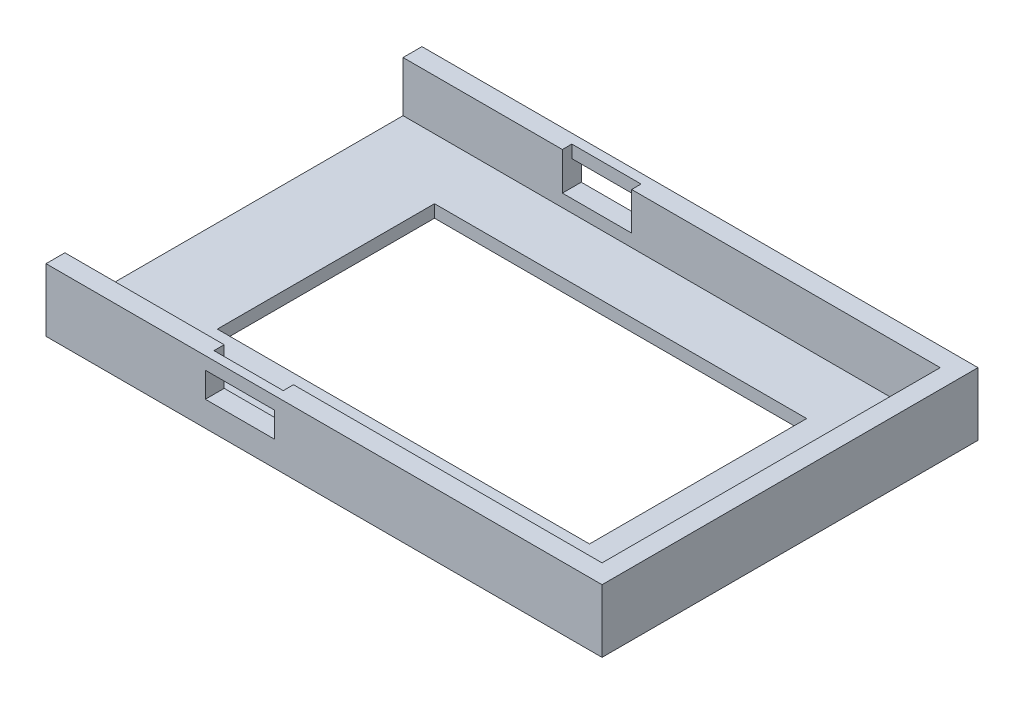
SolidWorks part; units mm, degrees
ref_plane "前视基准面" through (0, 0, 0) normal (0, 0, 1) x (1, 0, 0)
ref_plane "上视基准面" through (0, 0, 0) normal (0, 1, 0) x (1, 0, 0)
ref_plane "右视基准面" through (0, 0, 0) normal (1, 0, 0) x (0, 0, -1)
sketch "草图1" plane through (0, 0, 0) normal (0, 1, 0) x (1, 0, 0)
  line L0 (-41.15, -26.85) -> (41.15, -26.85)
  line L1 (-41.15, -26.85) -> (-41.15, 26.85)
  line L2 (41.15, -26.85) -> (41.15, 26.85)
  line L3 (-41.15, 26.85) -> (41.15, 26.85)
  line L4 (-41.15, -26.85) -> (41.15, 26.85) construction
  line L5 (41.15, -26.85) -> (-41.15, 26.85) construction
  line L6 (-44.15, -29.85) -> (44.15, -29.85)
  line L7 (-44.15, -29.85) -> (-44.15, 29.85)
  line L8 (44.15, -29.85) -> (44.15, 29.85)
  line L9 (-44.15, 29.85) -> (44.15, 29.85)
  line L10 (-44.15, -29.85) -> (44.15, 29.85) construction
  line L11 (44.15, -29.85) -> (-44.15, 29.85) construction
  point P1 (0, 0)
  point P2 (0, 0)
  dimension "D1" = 53.7
  dimension "D2" = 82.3
  dimension "D3" = 3
  dimension "D4" = 3
extrude "凸台-拉伸1" add sketch "草图1" along normal blind 8
sketch "草图2" plane through (0, 0, 0) normal (0, -1, 0) x (1, 0, 0)
  line L1 (-44.15, 29.85) -> (44.15, 29.85)
  line L2 (-44.15, 29.85) -> (-44.15, -29.85)
  line L3 (-44.15, -29.85) -> (44.15, -29.85)
  line L4 (44.15, 29.85) -> (44.15, -29.85)
extrude "凸台-拉伸2" add sketch "草图2" along normal blind 2
sketch "草图3" plane through (0, 0, 0) normal (0, 1, 0) x (1, 0, 0)
  line L0 (-29.5498, -17.245) -> (29.5498, -17.245)
  line L1 (-29.5498, -17.245) -> (-29.5498, 17.245)
  line L2 (29.5498, -17.245) -> (29.5498, 17.245)
  line L3 (-29.5498, 17.245) -> (29.5498, 17.245)
  line L4 (-29.5498, -17.245) -> (29.5498, 17.245) construction
  line L5 (29.5498, -17.245) -> (-29.5498, 17.245) construction
  point P1 (0, 0)
extrude "切除-拉伸1" cut sketch "草图3" against normal blind 2
sketch "草图4" plane through (0, 8, 0) normal (0, 1, 0) x (1, 0, 0)
  line L0 (-44.15, 29.85) -> (-44.15, -29.85) construction
  line L1 (-41.15, 26.85) -> (-44.15, 26.85)
  line L2 (-41.15, 26.85) -> (-41.15, -26.85)
  line L3 (-41.15, -26.85) -> (-44.15, -26.85)
  line L4 (-44.15, 26.85) -> (-44.15, -26.85)
  line L6 (-41.15, -26.85) -> (41.15, -26.85) construction
extrude "切除-拉伸2" cut sketch "草图4" against normal up to surface (8 mm away) up to face at (0, 0, 0)
sketch "草图5" plane through (0, 8, 0) normal (0, 1, 0) x (1, 0, 0)
  line L0 (-18.85, 29.85) -> (-18.85, 26.85)
  line L1 (44.15, 29.85) -> (-44.15, 29.85) construction
  line L2 (41.15, 26.85) -> (-44.15, 26.85) construction
  line L3 (-18.85, 26.85) -> (-7.85, 26.85)
  line L4 (41.15, 26.85) -> (-44.15, 26.85) construction
  line L5 (-7.85, 26.85) -> (-7.85, 29.85)
  line L6 (-7.85, 29.85) -> (-18.85, 29.85)
  line L7 (41.15, -26.85) -> (41.15, 26.85) construction
  line L8 (-66.2115, 0) -> (77.055, 0) construction
  line L9 (-7.85, -26.85) -> (-7.85, -29.85)
  line L10 (-18.85, -26.85) -> (-7.85, -26.85)
  line L11 (-18.85, -29.85) -> (-18.85, -26.85)
  line L12 (-7.85, -29.85) -> (-18.85, -29.85)
  dimension "D1" = 49
  dimension "D2" = 60
extrude "切除-拉伸3" cut sketch "草图5" against normal blind 6
sketch "草图6" plane through (-7.85, 0, 0) normal (-1, 0, 0) x (0, 0, 1)
  line L1 (29.85, 8) -> (28.4746, 8)
  line L2 (29.85, 8) -> (29.85, 6)
  line L3 (29.85, 6) -> (28.4746, 6)
  line L4 (28.4746, 8) -> (28.4746, 6)
  dimension "D1" = 2
extrude "凸台-拉伸3" add sketch "草图6" along normal up to surface (11 mm away) up to face at (-18.85, 5, 28.35)
sketch "草图7" plane through (-7.85, 0, 0) normal (-1, 0, 0) x (0, 0, 1)
  line L1 (-29.85, 8) -> (-28.35, 8)
  line L2 (-29.85, 8) -> (-29.85, 6)
  line L3 (-29.85, 6) -> (-28.35, 6)
  line L4 (-28.35, 8) -> (-28.35, 6)
  dimension "D1" = 2
  dimension "D2" = 1.5
extrude "凸台-拉伸4" add sketch "草图7" along normal up to next
